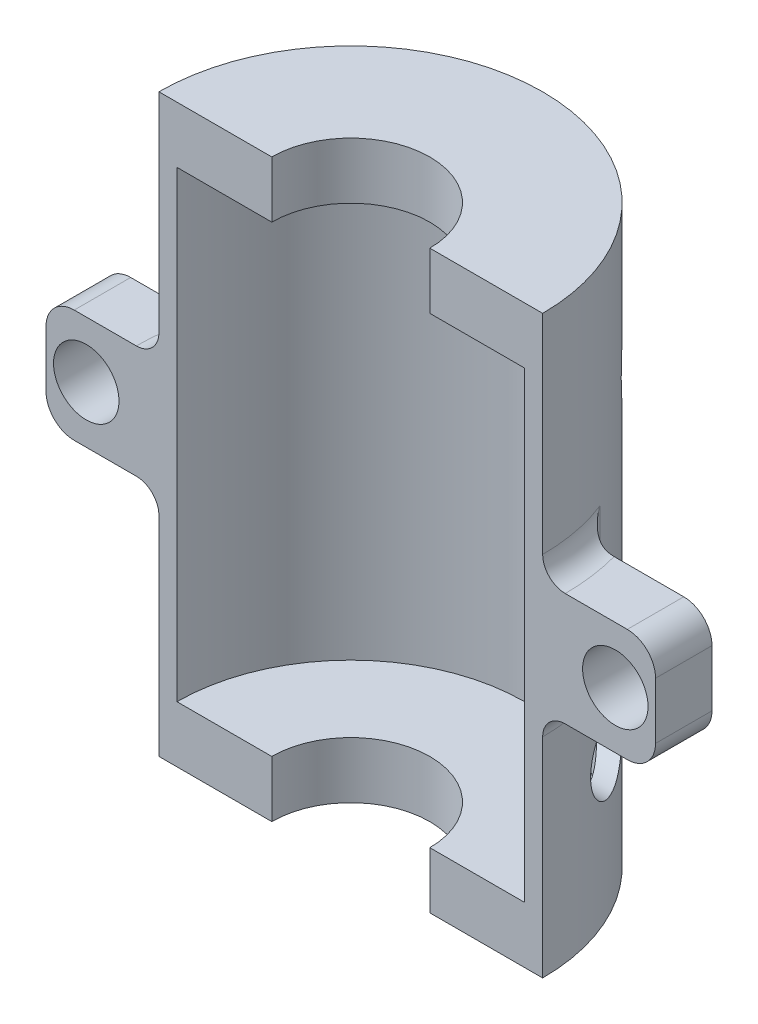
SolidWorks part; units mm, degrees
ref_plane "Front Plane" through (0, 0, 0) normal (0, 0, 1) x (1, 0, 0)
ref_plane "Top Plane" through (0, 0, 0) normal (0, 1, 0) x (1, 0, 0)
ref_plane "Right Plane" through (0, 0, 0) normal (1, 0, 0) x (0, 0, -1)
sketch "Sketch1" plane through (0, 0, 0) normal (0, 1, 0) x (1, 0, 0)
  line L0 (-15.4, 0) -> (-17, 0)
  line L1 (15.4, 0) -> (17, 0)
  circle A0 centre (0, 0) radius 15.4 construction
  circle A1 centre (0, 0) radius 17 construction
  arc A2 (-17, 0) -> (17, 0) centre (0, 0) cw
  arc A3 (-15.4, 0) -> (15.4, 0) centre (0, 0) cw
  dimension "D1" = 30.8
  dimension "D2" = 34
extrude "Boss-Extrude1" add sketch "Sketch1" along normal mid plane 41
sketch "Sketch6" plane through (0, 20.5, 0) normal (0, 1, 0) x (1, 0, 0)
  line L5 (-17, 0) -> (-7, 0)
  line L6 (7, 0) -> (17, 0)
  circle A0 centre (0, 0) radius 7 construction
  arc A2 (-7, 0) -> (7, 0) centre (0, 0) cw
  circle A4 centre (0, 0) radius 17 construction
  arc A5 (-17, 0) -> (17, 0) centre (0, 0) cw
  dimension "D1" = 14
extrude "Boss-Extrude2" add sketch "Sketch6" along normal blind 5
mirror "Mirror1" about plane through (0, 0, 0) normal (0, 1, 0) of "Boss-Extrude2"
sketch "Sketch7" plane through (0, 0, 0) normal (0, 1, 0) x (1, 0, 0)
  line L0 (-17, 0) -> (-27, 0)
  line L1 (-27, 0) -> (-27, 5)
  line L3 (-27, 5) -> (-16.2481, 5)
  arc A2 (17, 0) -> (-17, 0) centre (0, 0) ccw construction
  arc A3 (-16.2481, 5) -> (-17, 0) centre (0, 0) ccw
  point P10 (0, 0)
  point P11 (0, 0)
  dimension "D3" = 17
  dimension "D1" = 5
  dimension "D2" = 10
extrude "Boss-Extrude3" add sketch "Sketch7" along normal mid plane 10
fillet "Fillet1" radius 2 3 edges at (-16.811, -5, -2.5281) (-16.811, 5, -2.5281) (-16.2481, 0, -5)
sketch "Sketch8" plane through (0, 0, -5) normal (0, 0, -1) x (-1, 0, 0)
  circle A0 centre (23.4367, 0) radius 2.9
  dimension "D1" = 5.8
extrude "Cut-Extrude4" cut sketch "Sketch8" against normal mid plane 10
mirror "Mirror3" about plane through (0, 0, 0) normal (1, 0, 0) of "Cut-Extrude4", "Fillet1", "Boss-Extrude3"
fillet "Fillet2" radius 2.5 4 edges at (-27, -5, -2.5) (-27, 5, -2.5) (27, -5, -2.5) (27, 5, -2.5)
sketch "Sketch9" plane through (0, 0, 0) normal (1, 0, 0) x (0, 0, -1)
  line L2 (0, -7) -> (0, -25.5) construction
  line L3 (0, -25.5) -> (17, -25.5) construction
  circle A0 centre (8.5, -13) radius 3.5
  point P6 (19.6502, -8.8273)
  dimension "D1" = 7
  dimension "D2" = 8.5
  dimension "D3" = 12.5
extrude "Cut-Extrude5" cut sketch "Sketch9" along normal blind 50
sketch "Sketch11" plane through (0, 0, 0) normal (0, 0, 1) x (1, 0, 0)
  line L0 (0, 25.5) -> (0, -25.5)
  line L1 (7, 25.5) -> (-7, 25.5) construction
  line L2 (-7, -25.5) -> (7, -25.5) construction
ref_plane "Plane1" through (0, 0, 0) normal (-0.5, 0, 0.866) x (0, -1, 0)
sketch "Sketch17" plane through (0, 0, 0) normal (-0.5, 0, 0.866) x (0, -1, 0)
  line L0 (-25.5, 6.0622) -> (-25.5, -7) construction
  line L1 (-25.5, 14.7224) -> (-7, 14.7224) construction
  circle A0 centre (-13, 1.7224) radius 4
  dimension "D1" = 8
  dimension "D2" = 12.5
  dimension "D3" = 13
extrude "Cut-Extrude8" cut sketch "Sketch17" against normal blind 50
